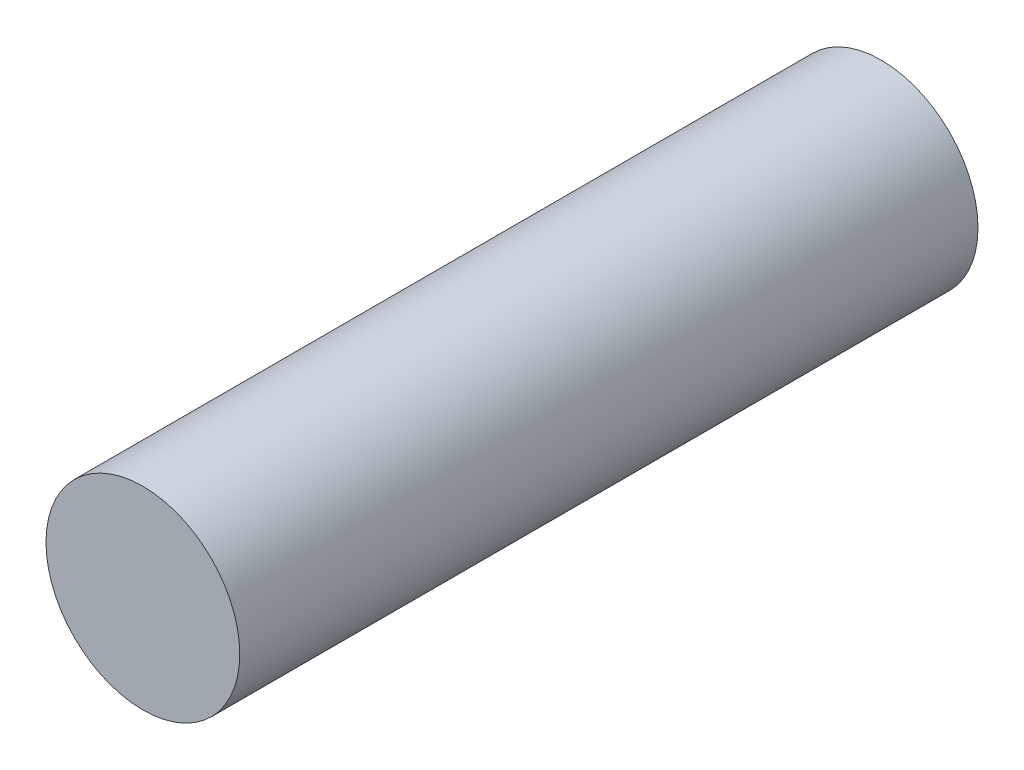
SolidWorks part; units mm, degrees
ref_plane "Front Plane" through (0, 0, 0) normal (0, 0, 1) x (1, 0, 0)
ref_plane "Top Plane" through (0, 0, 0) normal (0, 1, 0) x (1, 0, 0)
ref_plane "Right Plane" through (0, 0, 0) normal (1, 0, 0) x (0, 0, -1)
sketch "Sketch1" plane through (0, 0, 0) normal (0, 0, 1) x (1, 0, 0)
  circle A0 centre (0, 0) radius 2.5
  dimension "D1" = 5
extrude "Boss-Extrude1" add sketch "Sketch1" along normal blind 19.05
